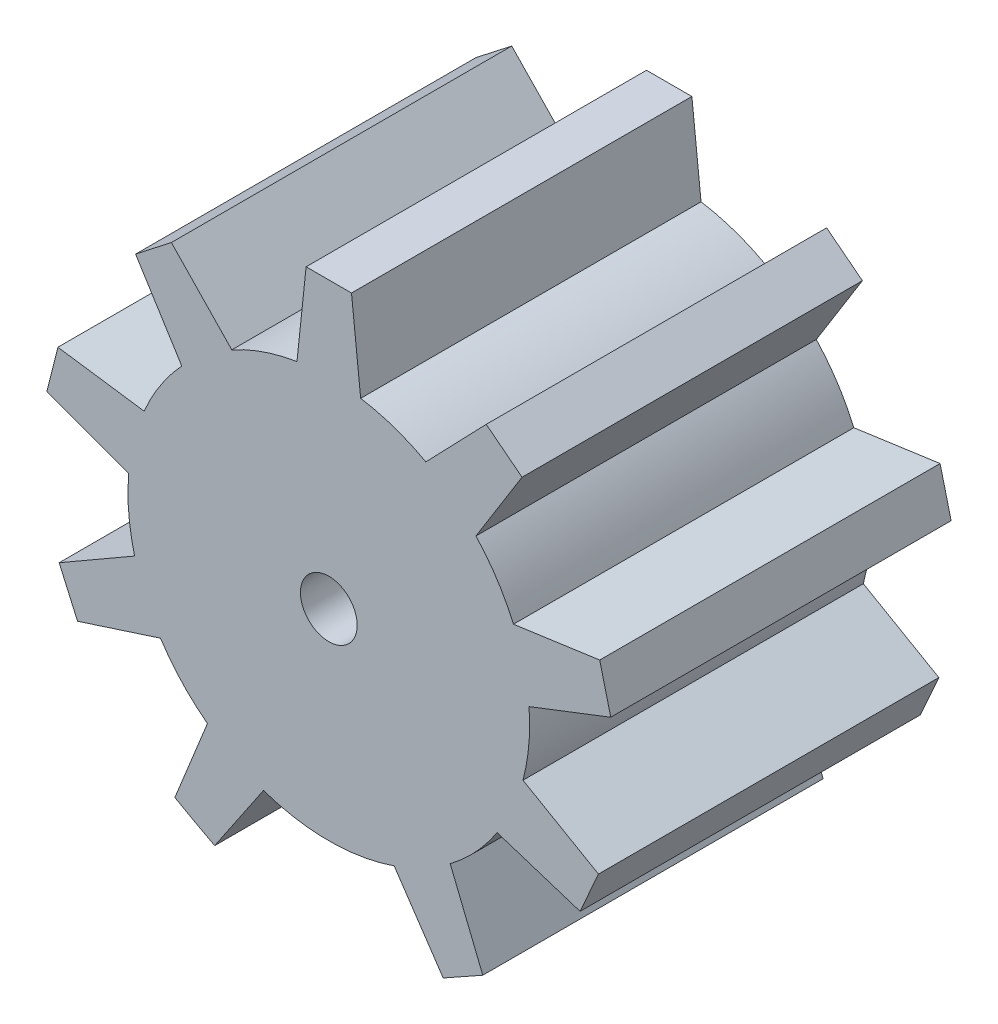
SolidWorks part; units mm, degrees
ref_plane "Спереди" through (0, 0, 0) normal (0, 0, 1) x (1, 0, 0)
ref_plane "Сверху" through (0, 0, 0) normal (0, 1, 0) x (1, 0, 0)
ref_plane "Справа" through (0, 0, 0) normal (1, 0, 0) x (0, 0, -1)
sketch "Эскиз3" plane through (0, 0, 0) normal (0, 0, 1) x (1, 0, 0)
  line B0 (0, 12.5567) -> (0, -11.4003) construction
  line B1 (-17.4471, 0) -> (17.8457, 0) construction
  line B2 (-1, 12.5567) -> (0, 12.5567)
  line B3 (0, 12.5567) -> (1, 12.5567)
  line B4 (-8.5148, 9.2827) -> (-6.9383, 10.5133)
  line B5 (-12.4239, 2.0778) -> (-11.9384, 4.018)
  line B6 (6.9383, 10.5133) -> (8.5148, 9.2827)
  line B7 (-11.883, -4.1789) -> (-11.0719, -6.007)
  line B8 (11.9384, 4.018) -> (12.4239, 2.0778)
  line B9 (11.0719, -6.007) -> (11.883, -4.1789)
  line B10 (-6.4791, 6.0286) -> (-8.5148, 9.2827)
  line B11 (-4.2757, 7.7486) -> (-6.9383, 10.5133)
  line B12 (-8.1384, 3.477) -> (-11.9384, 4.018)
  line B13 (-12.4239, 2.0778) -> (-8.8168, 0.7654)
  line B14 (-11.883, -4.1789) -> (-8.5563, -2.261)
  line B15 (-11.0719, -6.007) -> (-7.4176, -4.8272)
  line B16 (-1, 12.5567) -> (-1.4038, 8.738)
  line B17 (1, 12.5567) -> (1.4038, 8.738)
  line B18 (6.9383, 10.5133) -> (4.2757, 7.7486)
  line B19 (8.5148, 9.2827) -> (6.4833, 6.0241)
  line B20 (11.9384, 4.018) -> (8.1359, 3.4827)
  line B21 (12.4239, 2.0778) -> (8.8236, 0.6833)
  line B22 (11.883, -4.1789) -> (8.5563, -2.261)
  line B23 (11.0719, -6.007) -> (7.4176, -4.8272)
  arc B24 (-8.5563, -2.261) -> (-8.8168, 0.7654) centre (0, 0) cw
  arc B25 (-8.1384, 3.477) -> (-6.4791, 6.0286) centre (0, 0) cw
  arc B26 (-4.2757, 7.7486) -> (-1.4038, 8.738) centre (0, 0) cw
  arc B27 (1.4038, 8.738) -> (4.2757, 7.7486) centre (0, 0) cw
  arc B28 (6.4833, 6.0241) -> (8.1359, 3.4827) centre (0, 0) cw
  arc B29 (8.8236, 0.6833) -> (8.5563, -2.261) centre (0, 0) cw
  line B30 (-5.9113, -11.0782) -> (-6.7838, -10.5895)
  line B31 (-5.9113, -11.0782) -> (-5.0291, -11.549)
  line B32 (5.9134, -11.0771) -> (5.041, -11.5659)
  line B33 (2.8805, -8.3681) -> (5.041, -11.5659)
  line B34 (5.3502, -7.0497) -> (6.7858, -10.5883)
  line B35 (5.9134, -11.0771) -> (6.7858, -10.5883)
  line B36 (-6.7838, -10.5895) -> (-5.3488, -7.0507)
  line B37 (-2.879, -8.3686) -> (-5.0291, -11.549)
  arc B38 (-7.4176, -4.8272) -> (-5.3488, -7.0507) centre (0, 0) ccw
  arc B39 (-2.879, -8.3686) -> (2.8805, -8.3681) centre (0, 0) ccw
  arc B40 (5.3502, -7.0497) -> (7.4176, -4.8272) centre (0, 0) ccw
sketch_block_instance "Блок1-1"
sketch_block "Блок1" parameters "D1"=8.85
extrude "Бобышка-Вытянуть2" add sketch "Эскиз3" along normal blind 15
sketch "Эскиз5" plane through (0, 0, 0) normal (0, 0, -1) x (-1, 0, 0)
  circle A0 centre (0, 0) radius 1.25
extrude "Вырез-Вытянуть1" cut sketch "Эскиз5" against normal blind 15
